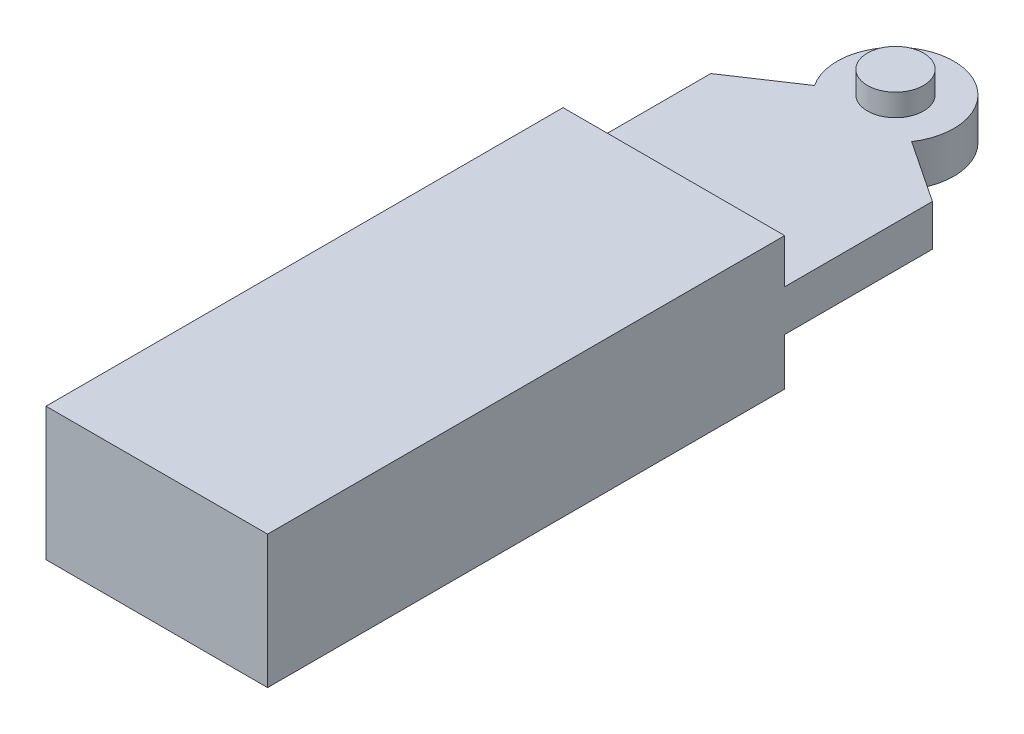
SolidWorks part; units mm, degrees
ref_plane "Front Plane" through (0, 0, 0) normal (0, 0, 1) x (1, 0, 0)
ref_plane "Top Plane" through (0, 0, 0) normal (0, 1, 0) x (1, 0, 0)
ref_plane "Right Plane" through (0, 0, 0) normal (1, 0, 0) x (0, 0, -1)
sketch "Sketch1" plane through (0, 0, 0) normal (0, 1, 0) x (1, 0, 0)
  circle A0 centre (0, 0) radius 39.5
  dimension "D1" = 79
extrude "Boss-Extrude1" add sketch "Sketch1" along normal blind 28
sketch "Sketch2" plane through (0, 28, 0) normal (0, 1, 0) x (1, 0, 0)
  circle A0 centre (0, 0) radius 19
  dimension "D1" = 38
extrude "Boss-Extrude2" add sketch "Sketch2" along normal blind 15 and the other way blind 45
sketch "Sketch3" plane through (0, 0, 0) normal (0, 1, 0) x (1, 0, 0)
  line L0 (0, 0) -> (-75, -50)
  line L2 (75, -50) -> (0, 0)
  line L3 (-75, -50) -> (-75, -500)
  line L4 (-75, -500) -> (75, -500)
  line L5 (75, -500) -> (75, -50)
  point P3 (0, 0)
  point P5 (0, -500)
  dimension "D1" = 450
  dimension "D2" = 150
  dimension "D3" = 50
extrude "Boss-Extrude3" add sketch "Sketch3" along normal up to surface (28 mm away) up to face at (0, 28, 19)
sketch "Sketch4" plane through (0, 28, 0) normal (0, 1, 0) x (1, 0, 0)
  line L1 (-75, -500) -> (75, -500)
  line L2 (-75, -500) -> (-75, -150)
  line L3 (-75, -150) -> (75, -150)
  line L4 (75, -500) -> (75, -150)
  point P6 (0, 0)
  dimension "D1" = 100
  dimension "D2" = 150
extrude "Boss-Extrude4" add sketch "Sketch4" along normal blind 30 and the other way blind 60
